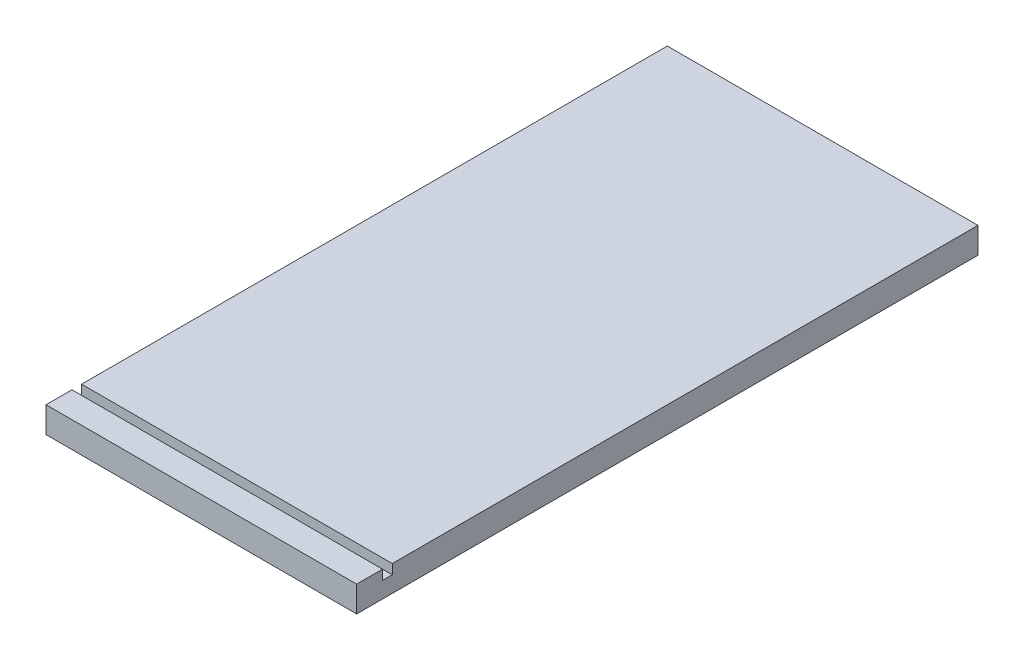
SolidWorks part; units mm, degrees
ref_plane "Front" through (0, 0, 0) normal (0, 0, 1) x (1, 0, 0)
ref_plane "Top" through (0, 0, 0) normal (0, 1, 0) x (1, 0, 0)
ref_plane "Right" through (0, 0, 0) normal (1, 0, 0) x (0, 0, -1)
sketch "Sketch2" plane through (0, 0, 0) normal (0, 1, 0) x (1, 0, 0)
  line L1 (-152.4, -304.8) -> (152.4, -304.8)
  line L2 (-152.4, -304.8) -> (-152.4, 304.8)
  line L3 (-152.4, 304.8) -> (152.4, 304.8)
  line L4 (152.4, -304.8) -> (152.4, 304.8)
  line L5 (-152.4, -304.8) -> (152.4, 304.8) construction
  line L6 (-152.4, 304.8) -> (152.4, -304.8) construction
  point P0 (0, 0)
  dimension "D1" = 304.8
  dimension "D2" = 609.6
extrude "Boss-Extrude1" add sketch "Sketch2" along normal mid plane 25.4 contours L3 L4 L1 L2
sketch "Sketch4" plane through (-152.4, 0, 0) normal (-1, 0, 0) x (0, 0, 1)
  line L0 (304.8, 12.7) -> (-304.8, 12.7) construction
  line L1 (279.4, 12.7) -> (269.875, 12.7)
  line L2 (279.4, 12.7) -> (279.4, 3.175)
  line L3 (279.4, 3.175) -> (269.875, 3.175)
  line L4 (269.875, 12.7) -> (269.875, 3.175)
  line L5 (304.8, 12.7) -> (304.8, -12.7) construction
  point P6 (274.6375, 3.175)
  dimension "D1" = 9.525
  dimension "D2" = 9.525
  dimension "D3" = 25.4
extrude "Cut-Extrude1" cut sketch "Sketch4" against normal through all contours L2 L3 L4 L1
